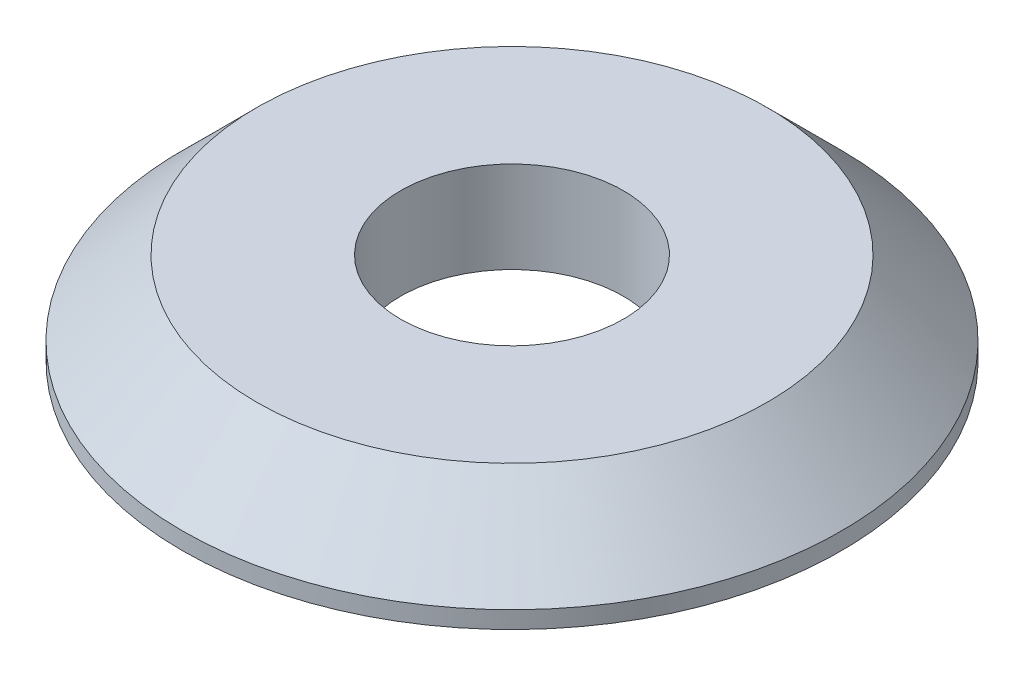
SolidWorks part; units mm, degrees
material "6061 Alloy"
ref_plane "Front" through (0, 0, 0) normal (0, 0, 1) x (1, 0, 0)
ref_plane "Top" through (0, 0, 0) normal (0, 1, 0) x (1, 0, 0)
ref_plane "Right" through (0, 0, 0) normal (1, 0, 0) x (0, 0, -1)
sketch "Sketch1" plane through (0, 0, 0) normal (0, 1, 0) x (1, 0, 0)
  circle A0 centre (0, 0) radius 3.048
  circle A1 centre (0, 0) radius 9.017
  dimension "D1" = 6.096
  dimension "D2" = 18.034
extrude "Boss-Extrude1" add sketch "Sketch1" along normal mid plane 2.5019
chamfer "Chamfer1" distance 2.032 angle 45 1 edges at (0, 1.251, 9.017)
